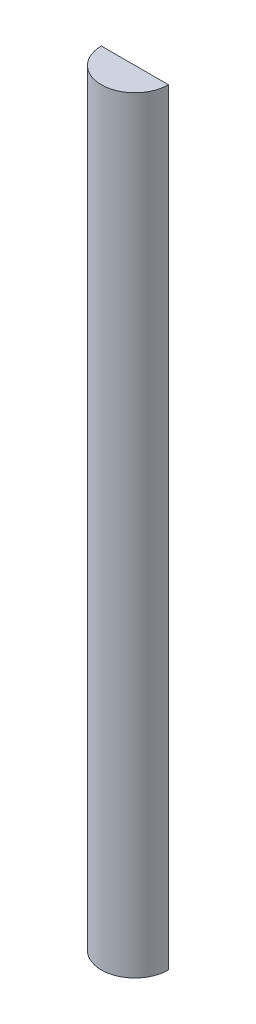
SolidWorks part; units mm, degrees
material "AISI 1020 Steel, Cold Rolled"
ref_plane "Front Plane" through (0, 0, 0) normal (0, 0, 1) x (1, 0, 0)
ref_plane "Top Plane" through (0, 0, 0) normal (0, 1, 0) x (1, 0, 0)
ref_plane "Right Plane" through (0, 0, 0) normal (1, 0, 0) x (0, 0, -1)
sketch "Sketch1" plane through (0, 0, 0) normal (0, 0, 1) x (1, 0, 0)
  line L1 (0, 0) -> (6.35, 0)
  line L2 (6.35, 0) -> (6.35, 145)
  line L3 (6.35, 145) -> (0, 145)
  line L4 (0, 140.4319) -> (0, -13.3662) construction
  line L5 (0, 145) -> (0, 0)
  dimension "D1" = 12.7
  dimension "D2" = 145
revolve "Revolve1" add sketch "Sketch1" angle 180 about L4
